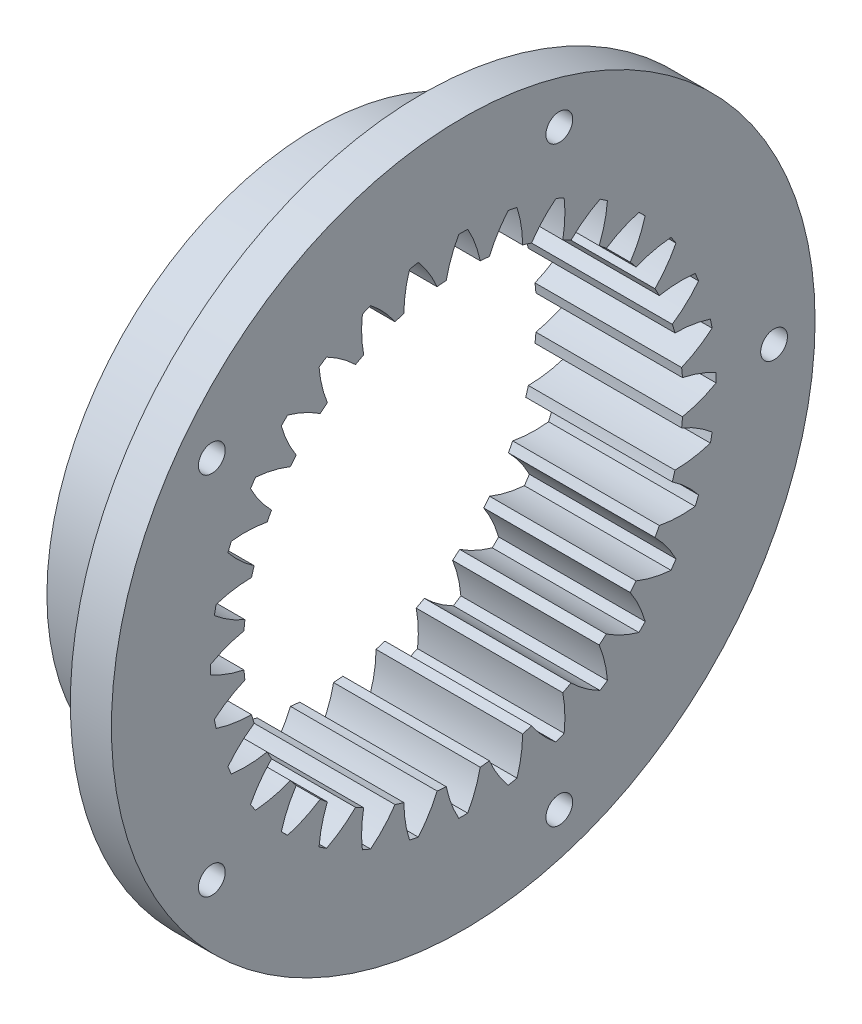
SolidWorks part; units mm, degrees
ref_plane "Plane1" through (0, 0, 0) normal (0, 0, 1) x (1, 0, 0)
ref_plane "Plane2" through (0, 0, 0) normal (0, 1, 0) x (1, 0, 0)
ref_plane "Plane3" through (0, 0, 0) normal (1, 0, 0) x (0, 0, -1)
sketch "HoldingSke" plane through (0, 0, 0) normal (0, 1, 0) x (1, 0, 0)
  line L0 (0, 0) -> (172.3234, -107.6796)
  line L1 (-15, 0) -> (100, 0) construction
  line L2 (0, 0) -> (-2.1039, 2.3779)
  line L3 (0, 0) -> (-11.863, 4.5341)
  line L4 (0, 0) -> (7.3237, 4.5764)
  line L5 (0, 0) -> (-23.7986, -8.8762)
  line L6 (0, 0) -> (-10.5278, -7.1032)
  line L7 (-2.1039, 2.3779) -> (3.3635, 27.1825)
  line L8 (-76.2, 54.61) -> (-54.61, 54.61)
  line L9 (-67.7845, 28.3722) -> (-49.3413, 33.142)
  line L10 (-76.2, 71.12) -> (104.1128, 71.12)
  line L11 (0, 0) -> (-31.75, 0)
  line L12 (-76.2, 101.6) -> (-76.0857, 101.6)
  line L13 (24.9733, 27.94) -> (52.9518, 28.4284)
  line L14 (24.9733, 27.94) -> (24.9746, 27.94)
  line L15 (24.9733, 27.94) -> (100.4006, 29.5858)
  circle A0 centre (0, 0) radius 12.7
  circle A1 centre (0, 0) radius 12.7
  circle A2 centre (0, 0) radius 12.7
  dimension "MHD" = 25.4
  dimension "Hub_dia" = 25.4
  dimension "Diameter" = 25.4
  dimension "Num_teeth" = 32
  dimension "Pitch" = 203.2
  dimension "Overall_len" = 25.4
  dimension "Show_teeth" = 32
  dimension "Thickness" = 12.7
  dimension "OAL" = 25.4001
  dimension "T_dim" = 21.59
  dimension "Ap" = 14.5
  dimension "H" = 19.05
  dimension "Pitch_radius" = 180.3128
  dimension "Width" = 31.75
  dimension "Backlash" = 0.1143
  dimension "Addendum_fac" = 1
  dimension "Dedendum_fac" = 1.25
  dimension "Clearance_fac" = 0.25
  dimension "Dedendum_add" = 0.0013
sketch "BasProSke" plane through (0, 0, 0) normal (0, 1, 0) x (1, 0, 0)
  line L0 (-10, 0) -> (60, 0) construction
  line L1 (0, 47.625) -> (0, 54.7954)
  line L2 (0, 47.625) -> (31.75, 47.625)
  line L3 (31.75, 47.625) -> (31.75, 54.7954)
  line L4 (31.75, 54.7954) -> (0, 54.7954)
  dimension "Thickness" = 31.75
  dimension "Diameter" = 109.5908
  dimension "Inside_diameter" = 95.25
revolve "Base-Revolve" add sketch "BasProSke" angle 360 about L0
sketch "TooCutSke" plane through (0, 0, 0) normal (1, 0, 0) x (0, 0, -1)
  line L3 (2.7784, 50.724) -> (2.7784, 53.6633) construction
  line L4 (0, 0) -> (0, 59.563) construction
  line L5 (0, 0) -> (-6.6973, 67.9985) construction
  line L6 (-21.2149, 42.3884) -> (33.322, 47.7598) construction
  circle A0 centre (0, 0) radius 50.8 construction
  circle A1 centre (0, 0) radius 54.77 construction
  circle A2 centre (0, 0) radius 44.2637 construction
  circle A3 centre (0, 0) radius 47.5996 construction
  arc A4 (3.6741, 47.4576) -> (0.9677, 54.7615) centre (-21.2149, 42.3884) ccw
  arc A5 (3.6741, 47.4576) -> (-3.6741, 47.4576) centre (0, 0) ccw
  arc A6 (0.9677, 54.7615) -> (-0.9677, 54.7615) centre (0, 0) ccw
  arc A7 (-0.9677, 54.7615) -> (-3.6741, 47.4576) centre (21.2149, 42.3884) ccw
  dimension "Pitch_dia" = 101.6
  dimension "Base_dia" = 88.5274
  dimension "Root_dia" = 109.54
  dimension "Overcut_dia" = 95.1992
  dimension "Flank_rad" = 25.4
  dimension "Half_ang" = 5.625
  dimension "Half_CT" = 2.7784
extrude "ToothCut" cut sketch "TooCutSke" along normal through all
fillet "Breaks" [suppressed] radius 0.3175
fillet "RootFillets" [suppressed] radius 0.795
pattern_circular "TeethCuts" count 32 every 11.25 about axis through (-10, 0, 0) along (1, 0, 0) of "RootFillets", "Breaks", "ToothCut"
sketch "Sketch1" plane through (0, 0, 0) normal (1, 0, 0) x (0, 0, -1)
  circle A0 centre (0, 0) radius 58.42
  circle A1 centre (0, 0) radius 54.7954 construction
  circle A2 centre (0, 0) radius 54.7954
  dimension "D1" = 116.84
extrude "Boss-Extrude2" add sketch "Sketch1" along normal up to surface (31.75 mm away) up to face at (31.75, 0, 54.7954)
sketch "Sketch3" plane through (31.75, 0, 0) normal (1, 0, 0) x (0, 0, -1)
  circle A0 centre (0, 0) radius 76.2
  circle A1 centre (0, 0) radius 58.42 construction
  circle A2 centre (0, 0) radius 58.42
  dimension "D1" = 152.4
extrude "Boss-Extrude4" add sketch "Sketch3" against normal blind 8.89
sketch "Sketch7" plane through (22.86, 0, 0) normal (-1, 0, 0) x (0, 0, 1)
  circle A3 centre (0, 0) radius 58.42 construction
  circle A4 centre (0, 0) radius 58.42 construction
  point P0 (-67.31, 0)
  dimension "D2" = 67.31
  dimension "D1" = 0
hole_wizard "CBORE for M5 Hex Head Bolt2" positions "3DSketch2" profile "Sketch8" counterbore size "M5" standard "ANSI Metric" end condition through all
sketch3d "3DSketch2"
  point P0 (22.86, 0, -67.31)
sketch "Sketch8" plane through (22.86, 0, -67.31) normal (0, 1, 0) x (0, 0, 1)
  line L0 (0, 0) -> (0, 8.89)
  line L1 (0, 8.89) -> (2.9, 8.89)
  line L3 (2.9, 8.89) -> (2.9, 3.58)
  line L4 (2.9, 3.58) -> (6.12, 3.58)
  line L5 (6.12, 3.58) -> (6.12, 0)
  line L7 (6.12, 0) -> (0, 0)
  line L11 (0, -6.35) -> (0, 107.95) construction
  dimension "Thru Hole Dia." = 5.8
  dimension "Thru Hole Depth" = 8.89
  dimension "C'Bore Dia." = 12.24
  dimension "C'Bore Depth" = 3.58
pattern_circular "CirPattern1" count 5 over 360 about axis through (0, 0, 0) along (1, 0, 0) of "CBORE for M5 Hex Head Bolt2"
sketch "Diam Pitch" plane through (0, 0, 0) normal (1, 0, 0) x (0, 0, -1)
  circle A0 centre (0, 0) radius 50.8 construction
  dimension "D1" = 101.6
equation "' \"Pitch@HoldingSke\" = 4"
equation "' \"Num_teeth@HoldingSke\" = 24"
equation "' \"Ap@HoldingSke\" =  14.5"
equation "' \"Ap@HoldingSke\" = 14.5"
equation "' \"Width@HoldingSke\" = 0.5"
equation "' \"Diameter@HoldingSke\" = 8"
equation "' \"Show_teeth@HoldingSke\" = 100"
equation "' \"Backlash@HoldingSke\" = 0.009"
equation "' \"Addendum_fac@HoldingSke\" = 1.0"
equation "' \"Dedendum_fac@HoldingSke\" = 1.25"
equation "' \"Dedendum_add@HoldingSke\" = 0.00005"
equation "' \"Clearance_fac@HoldingSke\" = 0.25"
equation "\"Overcut_dia@TooCutSke\" = (\"Num_teeth@HoldingSke\" - 2 * \"Addendum_fac@HoldingSke\") / \"Pitch@HoldingSke\" - 0.002"
equation "\"Pitch_dia@TooCutSke\" = \"Num_teeth@HoldingSke\" / \"Pitch@HoldingSke\""
equation "\"Base_dia@TooCutSke\" = \"Num_teeth@HoldingSke\" / \"Pitch@HoldingSke\" * cos((\"Ap@HoldingSke\"  * 3.14159265 / 180)) * 0.90"
equation "\"Root_dia@TooCutSke\" = \"Num_teeth@HoldingSke\"  / \"Pitch@HoldingSke\" + 2 *  \"Dedendum_fac@HoldingSke\"/ \"Pitch@HoldingSke\" + \"Dedendum_add@HoldingSke\" * 2"
equation "\"Half_ang@TooCutSke\" = 180 / \"Num_teeth@HoldingSke\""
equation "\"Half_CT@TooCutSke\" = \"Num_teeth@HoldingSke\" / \"Pitch@HoldingSke\" * sin((3.14159265 / 2 / \"Num_teeth@HoldingSke\")) / 2 + 10 * \"Backlash@HoldingSke\" / 4"
equation "\"Flank_rad@TooCutSke\" = \"Num_teeth@HoldingSke\" / \"Pitch@HoldingSke\" / 4"
equation "\"Radius@RootFillets\"= \"Clearance_fac@HoldingSke\" / \"Pitch@HoldingSke\" + \"Dedendum_add@HoldingSke\""
equation "\"Break_rad@Breaks\" = 0.02 / \"Pitch@HoldingSke\" * 5"
equation "\"Num_teeth@TeethCuts\" = int( \"Show_teeth@HoldingSke\" ) + 1"
equation "\"Num_teeth@TeethCuts\" = ((sgn( \"Num_teeth@TeethCuts\" - \"Num_teeth@HoldingSke\" )-1)*( \"Num_teeth@TeethCuts\" - \"Num_teeth@HoldingSke\" ))/-2+ \"Num_teeth@HoldingSke\""
equation "\"Num_teeth@TeethCuts\" = ((sgn( \"Num_teeth@TeethCuts\" - 2.0)+1)*( \"Num_teeth@TeethCuts\" - 2.0))/2 +2.0"
equation "\"Angle@TeethCuts\" = 360.0 / \"Num_teeth@HoldingSke\""
equation "\"Diameter@BasProSke\" = \"Num_teeth@HoldingSke\"  / \"Pitch@HoldingSke\" + 2 *  \"Dedendum_fac@HoldingSke\"/ \"Pitch@HoldingSke\" + \"Dedendum_add@HoldingSke\" * 2 + 0.002"
equation "\"Diameter@BasProSke\" = ((sgn( \"Diameter@BasProSke\"  - \"Diameter@HoldingSke\" )+1)*( \"Diameter@BasProSke\"  - \"Diameter@HoldingSke\" ))/2 + \"Diameter@HoldingSke\""
equation "\"Inside_diameter@BasProSke\" =  (\"Num_teeth@HoldingSke\" - 2 * \"Addendum_fac@HoldingSke\") / \"Pitch@HoldingSke\" "
equation "\"Thickness@BasProSke\"  = \"Width@HoldingSke\""
